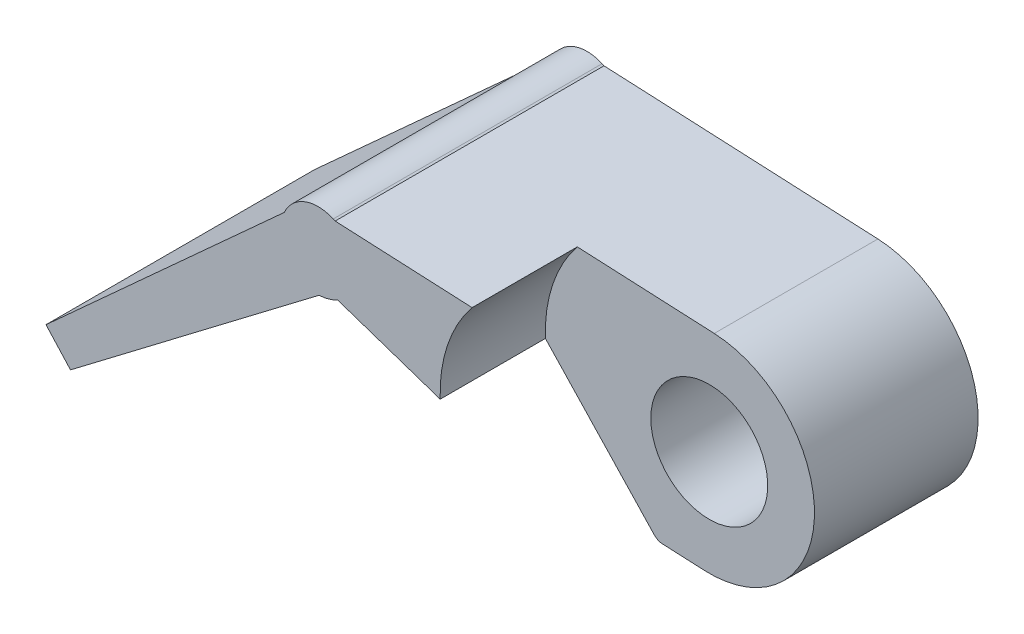
SolidWorks part; units mm, degrees
ref_plane "Front Plane" through (0, 0, 0) normal (0, 0, 1) x (1, 0, 0)
ref_plane "Top Plane" through (0, 0, 0) normal (0, 1, 0) x (1, 0, 0)
ref_plane "Right Plane" through (0, 0, 0) normal (1, 0, 0) x (0, 0, -1)
sketch "Sketch1" plane through (0, 0, 0) normal (0, 0, 1) x (1, 0, 0)
  line L0 (-26.2781, -11.3478) -> (-28.3722, -9.0438)
  line L1 (-28.3722, -9.0438) -> (-7.9902, 9.4622)
  line L2 (-3.8009, 11.0746) -> (-3.6375, 11.002)
  line L3 (-3.6375, 11.002) -> (19.794, 9.8897)
  line L4 (18.9406, -8.0881) -> (15.3487, -7.9165)
  line L5 (14.6682, -7.603) -> (5.3501, 2.2966)
  line L6 (5.3501, 2.2966) -> (-3.4192, 5.2559)
  line L7 (-5.0141, 4.8134) -> (-26.2781, -11.3478)
  arc A0 (-7.9902, 9.4622) -> (-3.8009, 11.0746) centre (-5.0894, 8.1738) cw
  arc A1 (19.794, 9.8897) -> (18.9406, -8.0881) centre (19.3673, 0.9008) cw
  arc A2 (15.3487, -7.9165) -> (14.6682, -7.603) centre (15.3965, -6.9175) cw
  arc A3 (-3.4192, 5.2559) -> (-5.0141, 4.8134) centre (-5.1897, 8.5415) cw
extrude "Boss-Extrude1" add sketch "Sketch1" along normal blind 23
ref_plane "Plane1" through (30, 0, 0) normal (1, 0, 0) x (0, 0, -1)
sketch "Sketch4" plane through (0, 0, 0) normal (0, 0, -1) x (-1, 0, 0)
  line L0 (-19.794, 9.8897) -> (-18.9406, -8.0881) construction
  line L1 (-28.3562, 0.4741) -> (-9.3065, 1.3784) construction
  arc A0 (-19.794, 9.8897) -> (-18.9406, -8.0881) centre (-19.3673, 0.9008) ccw construction
  circle A1 centre (-19.3673, 0.9008) radius 5
extrude "Cut-Extrude3" cut sketch "Sketch4" against normal blind 28
sketch "Sketch5" plane through (0, 0, 23) normal (0, 0, 1) x (1, 0, 0)
  line L2 (19.794, 9.8897) -> (-3.6375, 11.002) construction
  line L3 (8.0782, 10.4458) -> (19.794, 9.8897)
  line L4 (18.9406, -8.0881) -> (15.3487, -7.9165)
  line L5 (14.6682, -7.603) -> (5.3501, 2.2966)
  arc A0 (19.794, 9.8897) -> (18.9406, -8.0881) centre (19.3673, 0.9008) cw
  arc A2 (5.3501, 2.2966) -> (8.0782, 10.4458) centre (17.5838, 2.7324) cw
  arc A3 (15.3487, -7.9165) -> (14.6682, -7.603) centre (15.3965, -6.9175) cw
extrude "Cut-Extrude6" cut sketch "Sketch5" against normal blind 9
